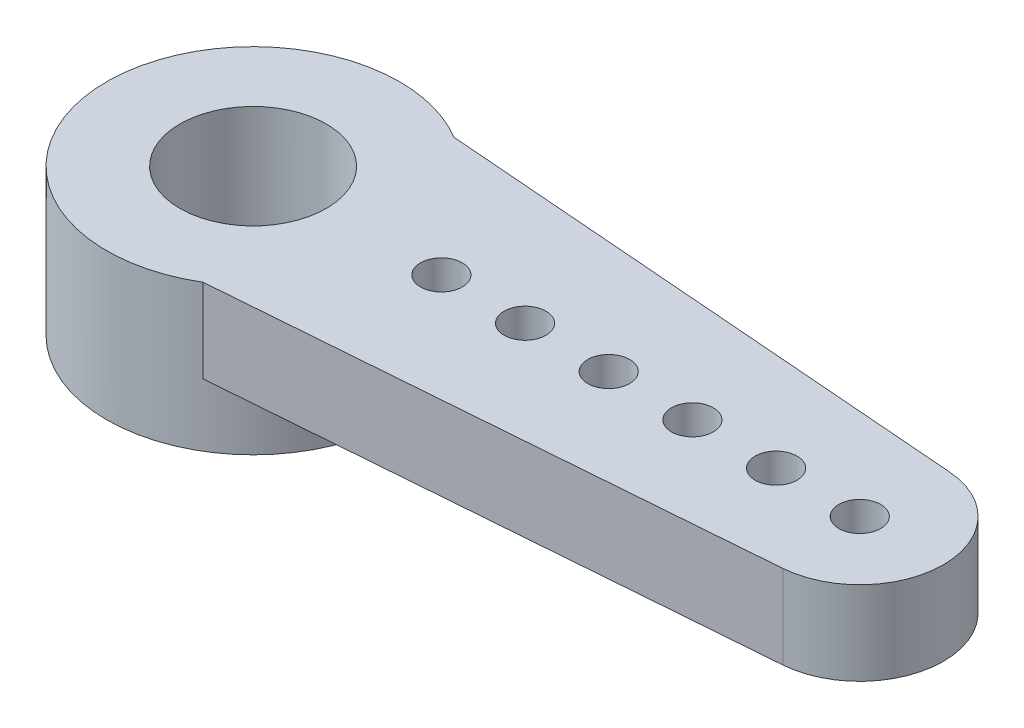
SolidWorks part; units mm, degrees
ref_plane "Front Plane" through (0, 0, 0) normal (0, 0, 1) x (1, 0, 0)
ref_plane "Top Plane" through (0, 0, 0) normal (0, 1, 0) x (1, 0, 0)
ref_plane "Right Plane" through (0, 0, 0) normal (1, 0, 0) x (0, 0, -1)
sketch "Sketch1" plane through (0, 0, 0) normal (0, 1, 0) x (1, 0, 0)
  line L0 (1.8028, 3) -> (14.6561, 1.9939)
  line L1 (1.8028, -3) -> (14.6561, -1.9939)
  arc A0 (1.8028, 3) -> (1.8028, -3) centre (0, 0) ccw
  arc A1 (14.6561, -1.9939) -> (14.6561, 1.9939) centre (14.5, 0) ccw
  dimension "D1" = 7
  dimension "D2" = 4
  dimension "D3" = 14.5
  dimension "D4" = 6
extrude "Boss-Extrude1" add sketch "Sketch1" along normal blind 2
sketch "Sketch2" plane through (0, 0, 0) normal (0, -1, 0) x (1, 0, 0)
  circle A0 centre (0, 0) radius 3.5
  dimension "D1" = 7
extrude "Boss-Extrude2" add sketch "Sketch2" along normal blind 1.5
sketch "Sketch3" plane through (0, 2, 0) normal (0, 1, 0) x (1, 0, 0)
  circle A0 centre (0, 0) radius 1.75
  dimension "D1" = 3.5
extrude "Cut-Extrude1" cut sketch "Sketch3" against normal blind 5
sketch "Sketch4" plane through (0, 2, 0) normal (0, 1, 0) x (1, 0, 0)
  circle A0 centre (4.5, 0) radius 0.5
  circle A1 centre (6.5, 0) radius 0.5
  circle A2 centre (8.5, 0) radius 0.5
  circle A3 centre (10.5, 0) radius 0.5
  circle A4 centre (12.5, 0) radius 0.5
  circle A5 centre (14.5, 0) radius 0.5
  dimension "D2" = 1
  dimension "D1" = 4.5
  dimension "D4" = 2
  dimension "D3" = 6
extrude "Cut-Extrude2" cut sketch "Sketch4" against normal blind 5
